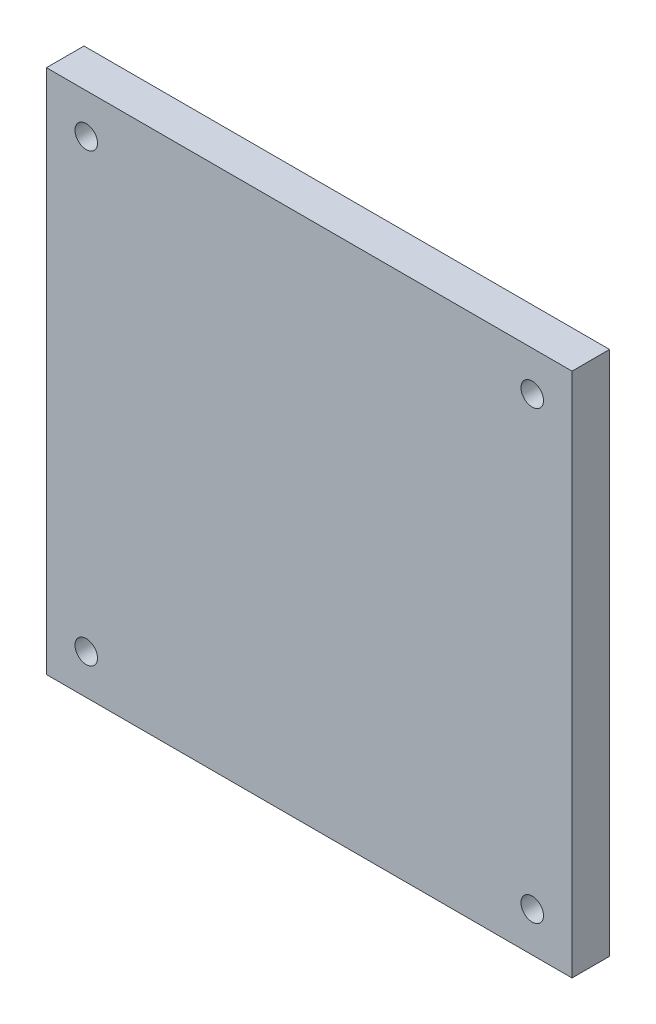
SolidWorks part; units mm, degrees
ref_plane "Спереди" through (0, 0, 0) normal (0, 0, 1) x (1, 0, 0)
ref_plane "Сверху" through (0, 0, 0) normal (0, 1, 0) x (1, 0, 0)
ref_plane "Справа" through (0, 0, 0) normal (1, 0, 0) x (0, 0, -1)
other "Configuration Table"
sketch "Эскиз1" plane through (0, 0, 0) normal (0, 0, 1) x (1, 0, 0)
  line L1 (-35, -35) -> (35, -35)
  line L2 (-35, -35) -> (-35, 35)
  line L3 (-35, 35) -> (35, 35)
  line L4 (35, -35) -> (35, 35)
  line L5 (-35, -35) -> (35, 35) construction
  line L6 (-35, 35) -> (35, -35) construction
  point P0 (0, 0)
  dimension "D1" = 70
  dimension "D2" = 70
extrude "Бобышка-Вытянуть1" add sketch "Эскиз1" along normal blind 5
sketch "Эскиз3" plane through (0, 0, 5) normal (0, 0, 1) x (1, 0, 0)
  line L0 (35, 35) -> (-35, 35) construction
  line L1 (-35, 35) -> (-35, -35) construction
  line L2 (0, -35) -> (0, 35) construction
  line L3 (-35, -35) -> (35, -35) construction
  line L4 (-35, 0) -> (35, 0) construction
  line L5 (35, -35) -> (35, 35) construction
  circle A0 centre (-29.7, 29.7) radius 1.5
  circle A1 centre (29.7, 29.7) radius 1.5
  circle A2 centre (29.7, -29.7) radius 1.5
  circle A3 centre (-29.7, -29.7) radius 1.5
  point P23 (0, 0)
  dimension "D4" = 3
  dimension "D5" = 3
  dimension "D1" = 5.3
  dimension "D2" = 5.3
  dimension "D3" = 4
extrude "Вырез-Вытянуть1" cut sketch "Эскиз3" against normal blind 5
